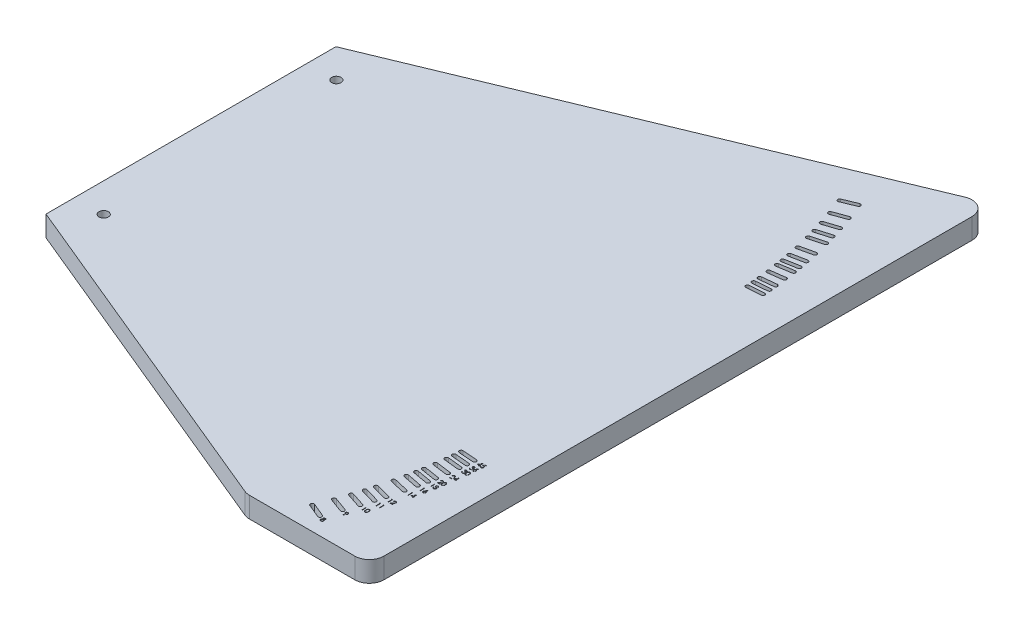
SolidWorks part; units mm, degrees
ref_plane "Front" through (0, 0, 0) normal (0, 0, 1) x (1, 0, 0)
ref_plane "Top" through (0, 0, 0) normal (0, 1, 0) x (1, 0, 0)
ref_plane "Right" through (0, 0, 0) normal (1, 0, 0) x (0, 0, -1)
sketch "Sketch1" plane through (0, 0, 0) normal (0, 1, 0) x (1, 0, 0)
  line L0 (0, 126.6361) -> (0, -126.6361)
  line L1 (0, -126.6361) -> (406.4, -294.9725)
  line L2 (406.4, -294.9725) -> (406.4, 294.9725)
  line L3 (406.4, 294.9725) -> (0, 126.6361)
  line L4 (25.4, 101.6) -> (25.4, -101.6) construction
  line L5 (25.4, 0) -> (0, 0) construction
  line L6 (25.4, 0) -> (406.4, 0) construction
  circle A0 centre (25.4, 101.6) radius 4.064
  circle A1 centre (25.4, -101.6) radius 4.064
  dimension "D1" = 8.128
  dimension "D2" = 203.2
  dimension "D3" = 112.5
  dimension "D4" = 25.4
  dimension "D5" = 406.4
extrude "Boss-Extrude1" add sketch "Sketch1" along normal blind 17.9832
sketch "Sketch2" plane through (0, 17.9832, 0) normal (0, 1, 0) x (1, 0, 0)
  line L0 (406.4, -294.9725) -> (406.4, 294.9725) construction
  line L1 (406.4, -250.5225) -> (299.0882, -250.5225)
  line L2 (406.4, -250.5225) -> (406.4, -294.9725)
  line L3 (406.4, -294.9725) -> (299.0882, -294.9725)
  line L4 (299.0882, -250.5225) -> (299.0882, -294.9725)
  line L5 (0, -126.6361) -> (406.4, -294.9725) construction
  dimension "D1" = 44.45
extrude "Cut-Extrude1" cut sketch "Sketch2" against normal blind 17.9832
fillet "Fillet1" radius 12.7 3 edges at (406.4, 8.9916, -294.9725) (406.4, 8.9916, 250.5225) (299.0882, 8.9916, 250.5225)
sketch "Sketch3" plane through (0, 17.9832, 0) normal (0, 1, 0) x (1, 0, 0)
  line L0 (25.4, -101.6) -> (364.0783, -155.2414) construction
  line L1 (25.4, -101.6) -> (361.7113, -168.4965) construction
  line L2 (25.4, 101.6) -> (25.4, -101.6) construction
  line L3 (25.4, -101.6) -> (342.1983, -232.8221) construction
  line L4 (25.4, 0) -> (406.4, 0) construction
  line L5 (406.4, -237.8225) -> (406.4, 275.9656) construction
  line L6 (25.4, -101.6) -> (354.4101, -198.2061) construction
  line L7 (25.4, -101.6) -> (356.616, -190.3491) construction
  line L8 (25.4, -101.6) -> (363.0906, -161.144) construction
  line L9 (25.4, -101.6) -> (347.6206, -218.8787) construction
  line L11 (348.0649, -235.2522) -> (336.3317, -230.3921) construction
  line L12 (25.4, -101.6) -> (351.5173, -207.5619) construction
  line L13 (347.4574, -236.7188) -> (335.7241, -231.8588)
  line L14 (348.6724, -233.7855) -> (336.9392, -228.9255)
  line L15 (353.5876, -221.0505) -> (341.6536, -216.7069) construction
  line L16 (353.0447, -222.5423) -> (341.1106, -218.1986)
  line L17 (354.1306, -219.5588) -> (342.1965, -215.2151)
  line L18 (357.5565, -209.5242) -> (345.4781, -205.5997) construction
  line L19 (357.0659, -211.034) -> (344.9875, -207.1095)
  line L20 (358.0471, -208.0144) -> (345.9686, -204.0899)
  line L21 (362.7496, -191.9926) -> (350.4823, -188.7055) construction
  line L22 (362.3387, -193.526) -> (350.0715, -190.239)
  line L23 (363.1605, -190.4591) -> (350.8932, -187.1721)
  line L27 (367.9393, -169.7353) -> (355.4833, -167.2576) construction
  line L28 (367.6296, -171.2923) -> (355.1736, -168.8146)
  line L29 (368.249, -168.1783) -> (355.793, -165.7007)
  line L30 (369.3441, -162.2466) -> (356.837, -160.0413) construction
  line L31 (369.0684, -163.81) -> (356.5614, -161.6047)
  line L32 (369.6198, -160.6832) -> (357.1127, -158.4779)
  line L33 (370.3502, -156.2347) -> (357.8065, -154.248) construction
  line L34 (370.1018, -157.8027) -> (357.5582, -155.816)
  line L35 (370.5985, -154.6668) -> (358.0549, -152.6801)
  line L36 (360.5029, -199.9951) -> (348.3174, -196.4171) construction
  line L37 (360.0557, -201.5183) -> (347.8701, -197.9403)
  line L38 (360.9502, -198.4719) -> (348.7646, -194.8939)
  line L47 (25.4, -101.6) -> (366.4216, -137.4428) construction
  line L48 (372.7368, -138.1066) -> (360.1063, -136.7791) construction
  line L49 (372.5708, -139.6854) -> (359.9404, -138.3579)
  line L50 (372.9027, -136.5278) -> (360.2723, -135.2003)
  line L51 (25.4, -101.6) -> (366.9952, -131.4857) construction
  line L54 (25.4, -101.6) -> (367.4647, -125.5195) construction
  line L55 (25.4, -101.6) -> (365.3664, -146.3574) construction
  line L56 (373.321, -132.0391) -> (360.6693, -130.9323) construction
  line L57 (373.1826, -133.6206) -> (360.531, -132.5137)
  line L58 (373.4594, -130.4577) -> (360.8077, -129.3508)
  line L59 (373.7992, -125.9624) -> (361.1302, -125.0765) construction
  line L60 (373.6885, -127.5461) -> (361.0194, -126.6602)
  line L61 (373.91, -124.3788) -> (361.2409, -123.4929)
  line L68 (371.6621, -147.1863) -> (359.0708, -145.5286) construction
  line L69 (371.4549, -148.7602) -> (358.8636, -147.1025)
  line L70 (371.8693, -145.6124) -> (359.278, -143.9547)
  line L71 (25.4, -101.6) -> (359.7028, -177.9024) construction
  line L72 (365.8936, -179.3154) -> (353.512, -176.4894) construction
  line L73 (365.5403, -180.8631) -> (353.1587, -178.0371)
  line L74 (366.2468, -177.7677) -> (353.8652, -174.9417)
  arc A0 (347.4574, -236.7188) -> (348.6724, -233.7855) centre (348.0649, -235.2522) ccw
  arc A1 (336.9392, -228.9255) -> (335.7241, -231.8588) centre (336.3317, -230.3921) ccw
  arc A2 (353.0447, -222.5423) -> (354.1306, -219.5588) centre (353.5876, -221.0505) ccw
  arc A3 (342.1965, -215.2151) -> (341.1106, -218.1986) centre (341.6536, -216.7069) ccw
  arc A4 (357.0659, -211.034) -> (358.0471, -208.0144) centre (357.5565, -209.5242) ccw
  arc A5 (345.9686, -204.0899) -> (344.9875, -207.1095) centre (345.4781, -205.5997) ccw
  arc A6 (362.3387, -193.526) -> (363.1605, -190.4591) centre (362.7496, -191.9926) ccw
  arc A7 (350.8932, -187.1721) -> (350.0715, -190.239) centre (350.4823, -188.7055) ccw
  arc A10 (367.6296, -171.2923) -> (368.249, -168.1783) centre (367.9393, -169.7353) ccw
  arc A11 (355.793, -165.7007) -> (355.1736, -168.8146) centre (355.4833, -167.2576) ccw
  arc A12 (369.0684, -163.81) -> (369.6198, -160.6832) centre (369.3441, -162.2466) ccw
  arc A13 (357.1127, -158.4779) -> (356.5614, -161.6047) centre (356.837, -160.0413) ccw
  arc A14 (370.1018, -157.8027) -> (370.5985, -154.6668) centre (370.3502, -156.2347) ccw
  arc A15 (358.0549, -152.6801) -> (357.5582, -155.816) centre (357.8065, -154.248) ccw
  arc A16 (360.0557, -201.5183) -> (360.9502, -198.4719) centre (360.5029, -199.9951) ccw
  arc A17 (348.7646, -194.8939) -> (347.8701, -197.9403) centre (348.3174, -196.4171) ccw
  arc A22 (372.5708, -139.6854) -> (372.9027, -136.5278) centre (372.7368, -138.1066) ccw
  arc A23 (360.2723, -135.2003) -> (359.9404, -138.3579) centre (360.1063, -136.7791) ccw
  arc A24 (373.1826, -133.6206) -> (373.4594, -130.4577) centre (373.321, -132.0391) ccw
  arc A25 (360.8077, -129.3508) -> (360.531, -132.5137) centre (360.6693, -130.9323) ccw
  arc A26 (373.6885, -127.5461) -> (373.91, -124.3788) centre (373.7992, -125.9624) ccw
  arc A27 (361.2409, -123.4929) -> (361.0194, -126.6602) centre (361.1302, -125.0765) ccw
  arc A32 (371.4549, -148.7602) -> (371.8693, -145.6124) centre (371.6621, -147.1863) ccw
  arc A33 (359.278, -143.9547) -> (358.8636, -147.1025) centre (359.0708, -145.5286) ccw
  arc A34 (365.5403, -180.8631) -> (366.2468, -177.7677) centre (365.8936, -179.3154) ccw
  arc A35 (353.8652, -174.9417) -> (353.1587, -178.0371) centre (353.512, -176.4894) ccw
  point P18 (342.1983, -232.8221)
  point P25 (347.6206, -218.8787)
  point P33 (351.5173, -207.5619)
  point P39 (356.616, -190.3491)
  point P53 (361.7113, -168.4965)
  point P61 (363.0906, -161.144)
  point P67 (364.0783, -155.2414)
  point P76 (354.4101, -198.2061)
  point P100 (366.4216, -137.4428)
  point P112 (366.9952, -131.4857)
  point P119 (367.4647, -125.5195)
  point P140 (365.3664, -146.3574)
  point P148 (359.7028, -177.9024)
  dimension "D1" = 342.9
  dimension "D3" = 20
  dimension "D4" = 18
  dimension "D5" = 15
  dimension "D2" = 22.5
  dimension "D7" = 11.25
  dimension "D8" = 10
  dimension "D9" = 9
  dimension "D10" = 12.7
  dimension "D11" = 3.175
  dimension "D13" = 16.364
  dimension "D18" = 4
  dimension "D19" = 5
  dimension "D20" = 6
  dimension "D21" = 7.5
  dimension "D22" = 12.857
extrude "Magic Cut" cut sketch "Sketch3" against normal through all
mirror "Mirror1" about plane through (0, 0, 0) normal (0, 0, 1) of "Magic Cut"
sketch "Sketch5" plane through (0, 17.9832, 0) normal (0, 1, 0) x (1, 0, 0)
  line L0 (348.0649, -235.2522) -> (350.7383, -238.7362) construction
  line L1 (357.5565, -209.5242) -> (360.495, -212.7877) construction
  line L2 (353.5876, -221.0505) -> (356.4105, -224.4146) construction
  line L3 (362.7496, -191.9926) -> (365.8549, -195.0978) construction
  line L4 (360.5029, -199.9951) -> (363.5334, -203.1734) construction
  line L5 (369.3441, -162.2466) -> (372.7082, -165.0694) construction
  line L6 (370.3502, -156.2347) -> (373.763, -158.9984) construction
  line L7 (371.6621, -147.1863) -> (375.1461, -149.8597) construction
  line L8 (367.9393, -169.7353) -> (371.241, -172.6308) construction
  line L9 (365.8936, -179.3154) -> (369.3795, -181.1578) construction
  line L10 (373.7992, -125.9624) -> (377.44, -128.4182) construction
  line L11 (373.321, -132.0391) -> (376.9183, -134.558) construction
  line L12 (372.7368, -138.1066) -> (376.2896, -140.6878) construction
  line L17 (348.0649, -235.2522) -> (336.3317, -230.3921) construction
  line L18 (353.5876, -221.0505) -> (341.6536, -216.7069) construction
  line L19 (357.5565, -209.5242) -> (345.4781, -205.5997) construction
  line L20 (360.5029, -199.9951) -> (348.3174, -196.4171) construction
  line L21 (362.7496, -191.9926) -> (350.4823, -188.7055) construction
  line L22 (365.8936, -179.3154) -> (353.512, -176.4894) construction
  line L23 (367.9393, -169.7353) -> (355.4833, -167.2576) construction
  line L24 (369.3441, -162.2466) -> (356.837, -160.0413) construction
  line L25 (370.3502, -156.2347) -> (357.8065, -154.248) construction
  line L26 (371.6621, -147.1863) -> (359.0708, -145.5286) construction
  line L27 (372.7368, -138.1066) -> (360.1063, -136.7791) construction
  line L28 (373.321, -132.0391) -> (360.6693, -130.9323) construction
  line L29 (373.7992, -125.9624) -> (361.1302, -125.0765) construction
  circle A0 centre (25.4, -101.6) radius 353.06 construction
  text T0 "8"
  text T1 "9"
  text T2 "10"
  text T3 "11"
  text T4 "12"
  text T5 "14"
  text T6 "16"
  text T7 "18"
  text T8 "20"
  text T9 "24"
  text T11 "30"
  text T12 "36"
  text T13 "45"
  dimension "D1" = 706.12
  dimension "D2" = 30
  dimension "D3" = 30
  dimension "D4" = 30
  dimension "D5" = 30
  dimension "D6" = 30
  dimension "D7" = 15
  dimension "D8" = 30
  dimension "D9" = 30
  dimension "D10" = 30
  dimension "D11" = 30
  dimension "D12" = 30
  dimension "D13" = 30
  dimension "D14" = 30
extrude "Cut-Extrude2" cut sketch "Sketch5" against normal blind 1.27
